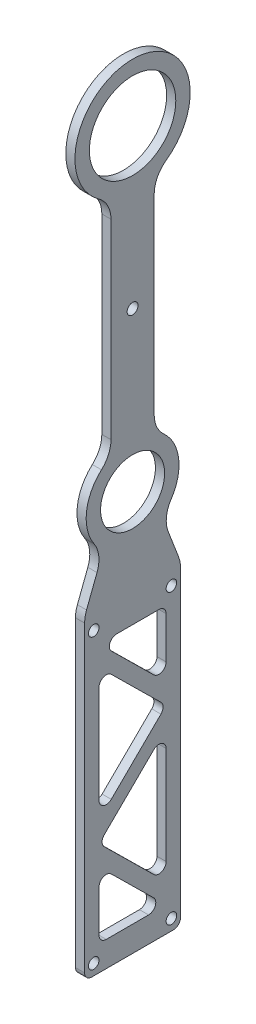
SolidWorks part; units mm, degrees
material "6061 Alloy"
ref_plane "Front Plane" through (0, 0, 0) normal (0, 0, 1) x (1, 0, 0)
ref_plane "Top Plane" through (0, 0, 0) normal (0, 1, 0) x (1, 0, 0)
ref_plane "Right Plane" through (0, 0, 0) normal (1, 0, 0) x (0, 0, -1)
sketch "Sketch1" plane through (0, 0, 0) normal (1, 0, 0) x (0, 0, -1)
  line L0 (-13.4747, 0) -> (13.4747, 0) construction
  line L1 (0, 0) -> (0, 35) construction
  line L2 (-13.4747, 0) -> (0, 35) construction
  line L3 (0, 35) -> (13.4747, 0) construction
  line L4 (13.4747, 0) -> (-13.4747, 0) construction
  line L5 (20.7574, -5) -> (-20.7574, -5)
  line L6 (-20.7574, -5) -> (-10.1693, 22.5021)
  line L7 (0, 48.9165) -> (1.1006, 46.0579) construction
  line L8 (0, 35) -> (0, 46.1125) construction
  line L9 (0, 35) -> (0, 46.1125) construction
  line L12 (-7.5, 35) -> (-7.5, 43.1999) construction
  line L13 (7.5, 35) -> (7.5, 43.1999) construction
  line L14 (-7.5, 35) -> (-7.5, 29.4356) construction
  line L15 (7.5, 35) -> (7.5, 29.4356) construction
  line L16 (-13.4747, 0) -> (13.4747, 0) construction
  line L17 (-13.4747, 0) -> (-13.4747, -100) construction
  line L18 (13.4747, 0) -> (13.4747, -100) construction
  line L19 (-13.4747, -100) -> (13.4747, -100) construction
  line L20 (-20.7574, -5) -> (20.7574, -5)
  line L21 (-20.7574, -5) -> (-20.7574, -103.81)
  line L22 (20.7574, -5) -> (20.7574, -103.81)
  line L23 (-20.7574, -103.81) -> (20.7574, -103.81)
  line L24 (-10.1693, 22.5021) -> (-8.2317, 27.535) construction
  line L25 (-7.5, 29.4356) -> (-6.6746, 31.5795) construction
  line L26 (-20.7574, -5) -> (0, 48.9165) construction
  line L27 (8.2317, 27.535) -> (10.1693, 22.5021) construction
  line L28 (10.1693, 22.5021) -> (20.7574, -5)
  line L29 (0, 48.9165) -> (20.7574, -5) construction
  line L30 (-7.5, 43.1999) -> (-7.5, 49.2605) construction
  line L31 (-7.5, 49.2605) -> (-7.5, 145)
  line L32 (7.5, 43.1999) -> (7.5, 49.2605) construction
  line L33 (7.5, 49.2605) -> (7.5, 145)
  line L34 (-8.2317, 27.535) -> (-7.5, 29.4356) construction
  line L35 (-6.6746, 31.5795) -> (-1.1006, 46.0579) construction
  line L36 (-1.1006, 46.0579) -> (0, 48.9165) construction
  line L37 (1.1006, 46.0579) -> (6.6746, 31.5795) construction
  line L38 (6.6746, 31.5795) -> (7.5, 29.4356) construction
  line L39 (7.5, 29.4356) -> (8.2317, 27.535) construction
  line L40 (0, 46.1125) -> (0, 48.9165) construction
  line L41 (0, 48.9165) -> (0, 145) construction
  line L42 (0, 46.1125) -> (0, 48.9165) construction
  line L43 (0, 48.9165) -> (0, 145) construction
  circle A0 centre (-13.4747, 0) radius 1.8288
  circle A1 centre (0, 35) radius 11.1125
  circle A2 centre (13.4747, 0) radius 1.8288
  circle A3 centre (0, 145) radius 3 construction
  arc A6 (-7.5, 35) -> (-6.6746, 31.5795) centre (0, 35) ccw construction
  arc A7 (7.5, 145) -> (-7.5, 145) centre (0, 145) ccw
  circle A8 centre (-13.4747, -100) radius 1.8288
  circle A9 centre (13.4747, -100) radius 1.8288
  circle A17 centre (0, 145) radius 15
  circle A18 centre (0, 145) radius 20
  arc A19 (10.1693, 22.5021) -> (7.5, 49.2605) centre (0, 35) ccw
  arc A20 (-10.1693, 22.5021) -> (-5.789, 19.9634) centre (0, 35) ccw construction
  circle A21 centre (0, 35) radius 16.1125 construction
  arc A22 (-5.789, 19.9634) -> (0, 18.8875) centre (0, 35) ccw construction
  arc A23 (0, 18.8875) -> (5.789, 19.9634) centre (0, 35) ccw construction
  arc A24 (5.789, 19.9634) -> (10.1693, 22.5021) centre (0, 35) ccw construction
  arc A25 (0, 51.1125) -> (-7.5, 49.2605) centre (0, 35) ccw construction
  arc A26 (-7.5, 49.2605) -> (-10.1693, 22.5021) centre (0, 35) ccw
  arc A27 (7.5, 49.2605) -> (0, 51.1125) centre (0, 35) ccw construction
  arc A28 (6.6746, 31.5795) -> (7.5, 35) centre (0, 35) ccw construction
  arc A29 (2.6946, 28.0008) -> (6.6746, 31.5795) centre (0, 35) ccw construction
  arc A30 (0, 27.5) -> (2.6946, 28.0008) centre (0, 35) ccw construction
  arc A31 (-2.6946, 28.0008) -> (0, 27.5) centre (0, 35) ccw construction
  arc A32 (-6.6746, 31.5795) -> (-2.6946, 28.0008) centre (0, 35) ccw construction
  point P4 (0, 0)
  point P14 (0, 90)
  point P34 (0, 145)
  dimension "D3" = 3.6576
  dimension "D4" = 22.225
  dimension "D7" = 6
  dimension "D11" = 5
  dimension "D13" = 30
  dimension "D14" = 40
  dimension "D1" = 26.9494
  dimension "D5" = 110
  dimension "D6" = 15
  dimension "D8" = 100
  dimension "D9" = 3.81
  dimension "D10" = 35
  dimension "D2" = 5
extrude "Boss-Extrude1" add sketch "Sketch1" along normal blind 3.175 contours L21 L23 L22 L5 A9 A8 | A6 L6 L5 L7 A2 A0 | L6 A6 L7 A1 | A18 L12 A6 L6 L7 L13 | A6 L7 L15 | A6 L14 L6 | L12 A18 L13 A17 | L13 A18 L12 A17
sketch "Sketch2" plane through (3.175, 0, 0) normal (1, 0, 0) x (0, 0, -1)
  line L0 (-11.645, -5) -> (11.645, -5) construction
  line L1 (-11.645, -95) -> (11.645, -95) construction
  line L2 (11.645, -95) -> (11.645, -5) construction
  line L3 (-11.645, -95) -> (-11.645, -5) construction
  line L6 (11.645, -38.5118) -> (-11.645, -61.4882) construction
  line L7 (11.645, -5) -> (-11.645, -5)
  line L8 (-11.645, -5) -> (11.645, -27.9764)
  line L9 (11.645, -27.9764) -> (11.645, -5)
  line L10 (-11.645, -12.0236) -> (11.645, -35)
  line L11 (11.645, -35) -> (-11.645, -57.9764)
  line L12 (-11.645, -57.9764) -> (-11.645, -35)
  line L13 (-11.645, -35) -> (-11.645, -12.0236)
  line L14 (-11.645, -72.0236) -> (-11.645, -95)
  line L15 (-11.645, -95) -> (11.645, -95)
  line L16 (11.645, -95) -> (-11.645, -72.0236)
  line L17 (11.645, -42.0236) -> (11.645, -65)
  line L18 (11.645, -65) -> (11.645, -87.9764)
  line L19 (11.645, -87.9764) -> (-11.645, -65)
  line L20 (-11.645, -65) -> (11.645, -42.0236)
  line L21 (16.645, -1056.0877) -> (16.645, 48943.9123) construction
  line L22 (-16.645, -1060.2922) -> (-16.645, 48939.7078) construction
  line L23 (16.645, 23.8875) -> (-16.645, 23.8875) construction
  line L24 (-20.7574, -103.81) -> (-16.645, -103.81)
  line L25 (-20.7574, -103.81) -> (-20.7574, 23.8875)
  line L26 (-16.645, -103.81) -> (-16.645, 23.8875)
  line L27 (-20.7574, 23.8875) -> (-16.645, 23.8875)
  line L28 (-20.7574, -103.81) -> (20.7574, -103.81) construction
  line L29 (20.7574, -103.81) -> (16.645, -103.81)
  line L30 (20.7574, -103.81) -> (20.7574, 23.8875)
  line L31 (16.645, -103.81) -> (16.645, 23.8875)
  line L32 (20.7574, 23.8875) -> (16.645, 23.8875)
  circle A0 centre (13.4747, 0) radius 1.8288 construction
  circle A1 centre (13.4747, -100) radius 1.8288 construction
  circle A2 centre (0, 35) radius 11.1125 construction
  point P6 (11.645, -50)
  point P10 (0, 23.8875)
  point P21 (0, -50)
  dimension "D1" = 33.29
  dimension "D2" = 5
  dimension "D3" = 5
  dimension "D4" = 5
  dimension "D5" = 5
  dimension "D6" = 2.5
  dimension "D8" = 5
  dimension "D7" = 2
extrude "Cut-Extrude1" cut sketch "Sketch2" against normal up to next
fillet "Fillet3" radius 2.5 14 edges at (1.5875, -57.9764, 11.645) (1.5875, -35, -11.645) (1.5875, -95, -11.645) (1.5875, -72.0236, 11.645) (1.5875, -95, 11.645) (1.5875, -27.9764, -11.645) (1.5875, -5, -11.645) (1.5875, -12.0236, 11.645) (1.5875, -5, 11.645) (1.5875, -87.9764, -11.645) (1.5875, -42.0236, -11.645) (1.5875, -65, 11.645) (1.5875, -103.81, -16.645) (1.5875, -103.81, 16.645)
fillet "Fillet4" radius 10 8 edges at (1.5875, 5.6818, 16.645) (1.5875, 5.6818, -16.645) (1.5875, 126.4595, 7.5) (1.5875, 126.4595, -7.5) (1.5875, 49.2605, -7.5) (1.5875, 49.2605, 7.5) (1.5875, 22.5021, 10.1693) (1.5875, 22.5021, -10.1693)
hole_wizard "#6 Clearance Hole1" positions "Sketch3" profile "Sketch4" hole size "#6" standard "ANSI Inch" end condition up to next
sketch "Sketch3" plane through (3.175, 0, 0) normal (1, 0, 0) x (0, 0, -1)
  circle A0 centre (0, 35) radius 11.1125 construction
  point P0 (0, 90)
  dimension "D1" = 55
sketch "Sketch4" plane through (3.175, 90, 0) normal (0, 1, 0) x (0, 0, -1)
  line L0 (0, 0) -> (0, 3.175)
  line L1 (0, 3.175) -> (1.8986, 3.175)
  line L2 (1.8986, 3.175) -> (1.8986, 0)
  line L5 (1.8986, 0) -> (0, 0)
  line L11 (0, -6.35) -> (0, 107.95) construction
  dimension "Thru Hole Dia." = 3.7973
  dimension "Thru Hole Depth" = 3.175
